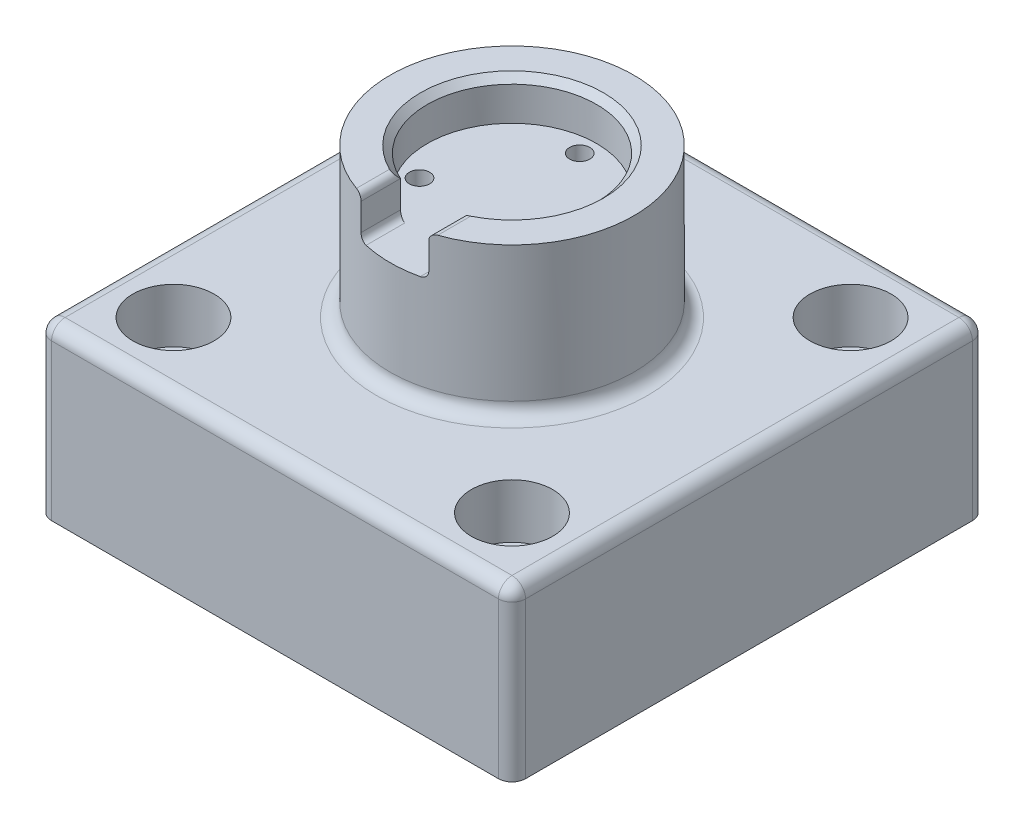
SolidWorks part; units mm, degrees
ref_plane "前视基准面" through (0, 0, 0) normal (0, 0, 1) x (1, 0, 0)
ref_plane "上视基准面" through (0, 0, 0) normal (0, 1, 0) x (1, 0, 0)
ref_plane "右视基准面" through (0, 0, 0) normal (1, 0, 0) x (0, 0, -1)
sketch "草图1" plane through (0, 0, 0) normal (0, 1, 0) x (1, 0, 0)
  line L0 (-35, 35) -> (35, 35)
  line L1 (-25, -25) -> (25, -25)
  line L2 (-25, -25) -> (-25, 25)
  line L3 (-25, 25) -> (25, 25)
  line L4 (25, -25) -> (25, 25)
  line L5 (-25, -25) -> (25, 25) construction
  line L6 (-25, 25) -> (25, -25) construction
  line L7 (35, -35) -> (35, 35)
  line L8 (-35, -35) -> (35, -35)
  line L9 (-35, -35) -> (-35, 35)
  point P0 (0, 0)
  dimension "D1" = 50
  dimension "D2" = 50
  dimension "D3" = 10
extrude "凸台-拉伸1" add sketch "草图1" along normal blind 25 contours L9 L8 L7 L0 L4 L1 L2 L3
sketch "草图2" plane through (0, 25, 0) normal (0, 1, 0) x (1, 0, 0)
  circle A0 centre (0, 0) radius 18
  dimension "D1" = 36
extrude "凸台-拉伸2" add sketch "草图2" along normal blind 22
sketch "草图3" plane through (0, 47, 0) normal (0, 1, 0) x (1, 0, 0)
  circle A0 centre (0, 0) radius 12.5
  dimension "D1" = 25
extrude "切除-拉伸1" cut sketch "草图3" against normal blind 6
sketch "草图5" plane through (0, 41, 0) normal (0, 1, 0) x (1, 0, 0)
  line L0 (0, 19.8339) -> (0, -22.1836) construction
  line L1 (-25.9506, 0) -> (33.2072, 0) construction
  circle A0 centre (0, 0) radius 10 construction
  circle A1 centre (0, 10) radius 1.5
  circle A2 centre (8.6603, -5) radius 1.5
  circle A3 centre (-8.6603, -5) radius 1.5
  point P8 (0, 10)
  dimension "D1" = 20
  dimension "D2" = 3
  dimension "D3" = 3
extrude "切除-拉伸2" cut sketch "草图5" against normal through all contours A1 | A3 | A2
sketch "草图6" plane through (0, 0, 0) normal (0, 0, 1) x (1, 0, 0)
  line L0 (12.5, 47) -> (-12.5, 47) construction
  line L1 (-5, 53) -> (5, 53)
  line L2 (-5, 53) -> (-5, 41)
  line L3 (-5, 41) -> (5, 41)
  line L4 (5, 53) -> (5, 41)
  line L5 (-5, 53) -> (5, 41) construction
  line L6 (-5, 41) -> (5, 53) construction
  point P0 (0, 47)
  dimension "D1" = 10
  dimension "D2" = 12
extrude "切除-拉伸3" cut sketch "草图6" along normal blind 20
sketch "草图7" plane through (0, 0, 0) normal (0, 1, 0) x (1, 0, 0)
  line L1 (-25, -25) -> (25, -25) construction
  line L2 (-25, -25) -> (-25, 25) construction
  line L3 (-25, 25) -> (25, 25) construction
  line L4 (25, -25) -> (25, 25) construction
  line L5 (-25, -25) -> (25, 25) construction
  line L6 (-25, 25) -> (25, -25) construction
  circle A0 centre (-25, 25) radius 3
  circle A1 centre (25, 25) radius 3
  circle A2 centre (25, -25) radius 3
  circle A3 centre (-25, -25) radius 3
  point P0 (0, 0)
  dimension "D3" = 6
  dimension "D4" = 6
  dimension "D5" = 6
  dimension "D6" = 6
  dimension "D1" = 50
  dimension "D2" = 50
extrude "切除-拉伸4" cut sketch "草图7" along normal through all contours A0 | A3 | A2 | A1
sketch "草图8" plane through (0, 25, 0) normal (0, 1, 0) x (1, 0, 0)
  line L0 (0, 22.7725) -> (0, -29.8372) construction
  line L1 (-29.1738, 0) -> (32.5329, 0) construction
  circle A0 centre (-25, 25) radius 6
  circle A1 centre (25, 25) radius 6
  circle A2 centre (25, -25) radius 6
  circle A3 centre (-25, -25) radius 6
  dimension "D1" = 12
extrude "切除-拉伸5" cut sketch "草图8" against normal blind 8
sketch "草图9" plane through (0, 0, 0) normal (0, -1, 0) x (1, 0, 0)
  line L1 (-18, 18) -> (18, 18)
  line L2 (-18, 18) -> (-18, -18)
  line L3 (-18, -18) -> (18, -18)
  line L4 (18, 18) -> (18, -18)
  line L5 (-18, 18) -> (18, -18) construction
  line L6 (-18, -18) -> (18, 18) construction
  point P0 (0, 0)
  dimension "D1" = 36
  dimension "D2" = 36
extrude "切除-拉伸6" cut sketch "草图9" against normal blind 12
fillet "圆角1" radius 2 15 edges at (0, 12, -18) (18, 12, 0) (0, 12, 18) (-18, 12, 0) (-18, 6, -18) (18, 6, -18) (18, 6, 18) (0, 25, 35) (35, 25, 0) (0, 25, -35) (-35, 25, 0) (-35, 12.5, -35) (35, 12.5, -35) (35, 12.5, 35) (-35, 12.5, 35)
fillet "圆角2" radius 2 1 edges at (0, 25, 18)
chamfer "倒角1" distance 1 angle 45 1 edges at (0, 47, -12.5)
fillet "圆角3" radius 1 4 edges at (-5, 47, 14.9158) (5, 47, 14.9158) (5, 41, 14.374) (-5, 41, 14.374)
